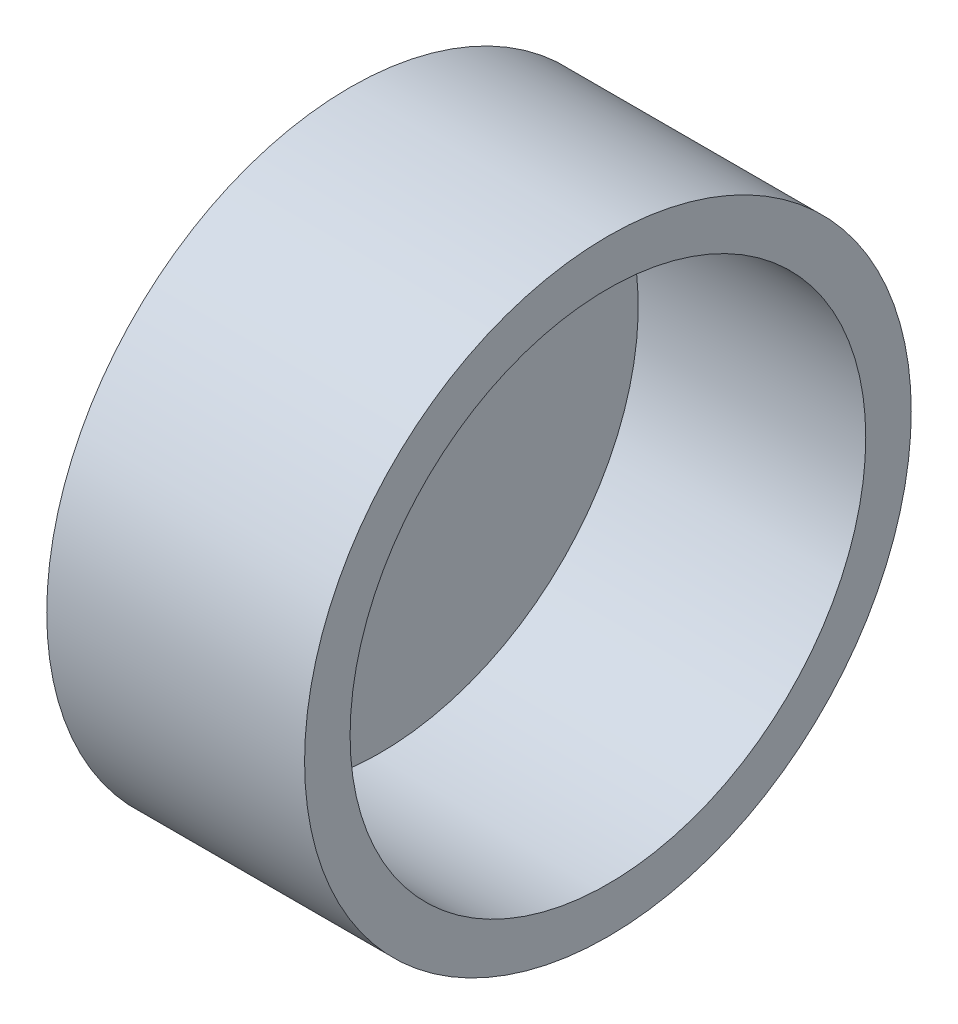
SolidWorks part; units mm, degrees
ref_plane "正面" through (0, 0, 0) normal (1, 0, 0) x (0, 1, 0)
ref_plane "平面" through (0, 0, 0) normal (0, 0, 1) x (0, 1, 0)
ref_plane "右側面" through (0, 0, 0) normal (0, 1, 0) x (-1, 0, 0)
sketch "ｽｹｯﾁ1" plane through (0, 0, 0) normal (1, 0, 0) x (0, 1, 0)
  circle A0 centre (0, 0) radius 10
  circle A1 centre (0, 0) radius 8.5
  dimension "D1" = 20
  dimension "D2" = 17
extrude "ﾎﾞｽ - 押し出し1" add sketch "ｽｹｯﾁ1" along normal blind 8.5 contours A1 | A0
sketch "ｽｹｯﾁ2" plane through (0, 0, 0) normal (-1, 0, 0) x (0, -1, 0)
  circle A0 centre (0, 0) radius 8.5
  circle A1 centre (0, 0) radius 1.5
  dimension "D1" = 3
extrude "ﾎﾞｽ - 押し出し2" add sketch "ｽｹｯﾁ2" against normal blind 1 contours A0
sketch "ｽｹｯﾁ7" plane through (0, 0, 0) normal (-1, 0, 0) x (0, -1, 0)
  circle A0 centre (0, 0) radius 1.5
  dimension "D1" = 3
extrude "ｶｯﾄ - 押し出し3" cut sketch "ｽｹｯﾁ7" against normal through all
